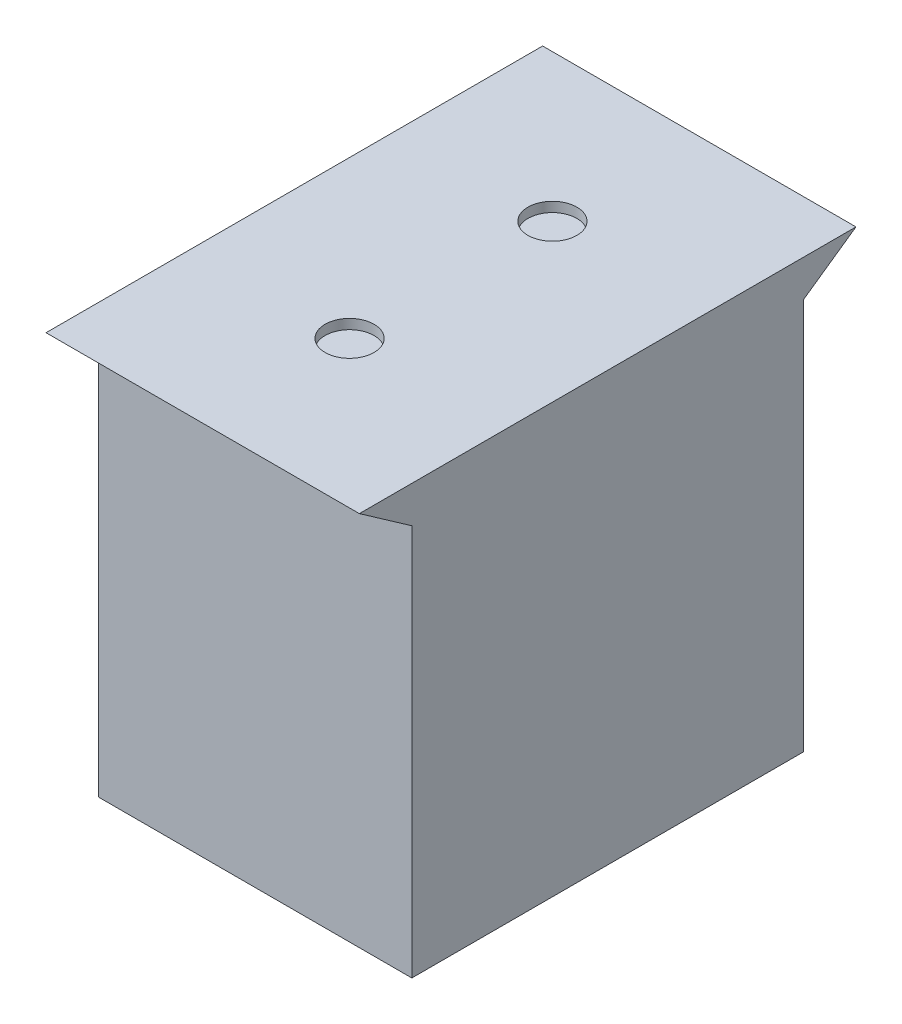
SolidWorks part; units mm, degrees
ref_plane "Front Plane" through (0, 0, 0) normal (0, 0, 1) x (1, 0, 0)
ref_plane "Top Plane" through (0, 0, 0) normal (0, 1, 0) x (1, 0, 0)
ref_plane "Right Plane" through (0, 0, 0) normal (1, 0, 0) x (0, 0, -1)
sketch "Sketch1" plane through (0, 0, 0) normal (0, 1, 0) x (1, 0, 0)
  line L1 (-2.032, 2.54) -> (2.032, 2.54)
  line L2 (-2.032, 2.54) -> (-2.032, -2.54)
  line L3 (-2.032, -2.54) -> (2.032, -2.54)
  line L4 (2.032, 2.54) -> (2.032, -2.54)
  line L5 (-2.032, 2.54) -> (2.032, -2.54) construction
  line L6 (-2.032, -2.54) -> (2.032, 2.54) construction
  point P0 (0, 0)
  dimension "D1" = 4.064
  dimension "D2" = 5.08
extrude "Boss-Extrude1" add sketch "Sketch1" along normal blind 5.08
sketch "Sketch4" plane through (-2.032, 0, 0) normal (-1, 0, 0) x (0, 0, 1)
  line L0 (-2.54, 5.08) -> (-3.2206, 5.5565)
  line L1 (-3.2206, 5.5565) -> (3.2206, 5.5565)
  line L2 (3.2206, 5.5565) -> (2.54, 5.08)
  line L3 (2.54, 5.08) -> (-2.54, 5.08)
  dimension "D1" = 35
  dimension "D2" = 35
extrude "Boss-Extrude3" add sketch "Sketch4" against normal up to surface (4.064 mm away) up to face at (2.032, 2.54, 0)
sketch "Sketch5" plane through (0, 5.5565, 0) normal (0, 1, 0) x (1, 0, 0)
  line L0 (2.032, 3.2206) -> (-2.032, 3.2206) construction
  line L1 (-2.2352, 0) -> (2.2352, 0) construction
  circle A0 centre (0, 1.3156) radius 0.3175
  circle A1 centre (0, -1.3156) radius 0.3175
  dimension "D2" = 0.635
  dimension "D1" = 1.905
extrude "Cut-Extrude2" cut sketch "Sketch5" against normal blind 0.127 contours A0 | A1
